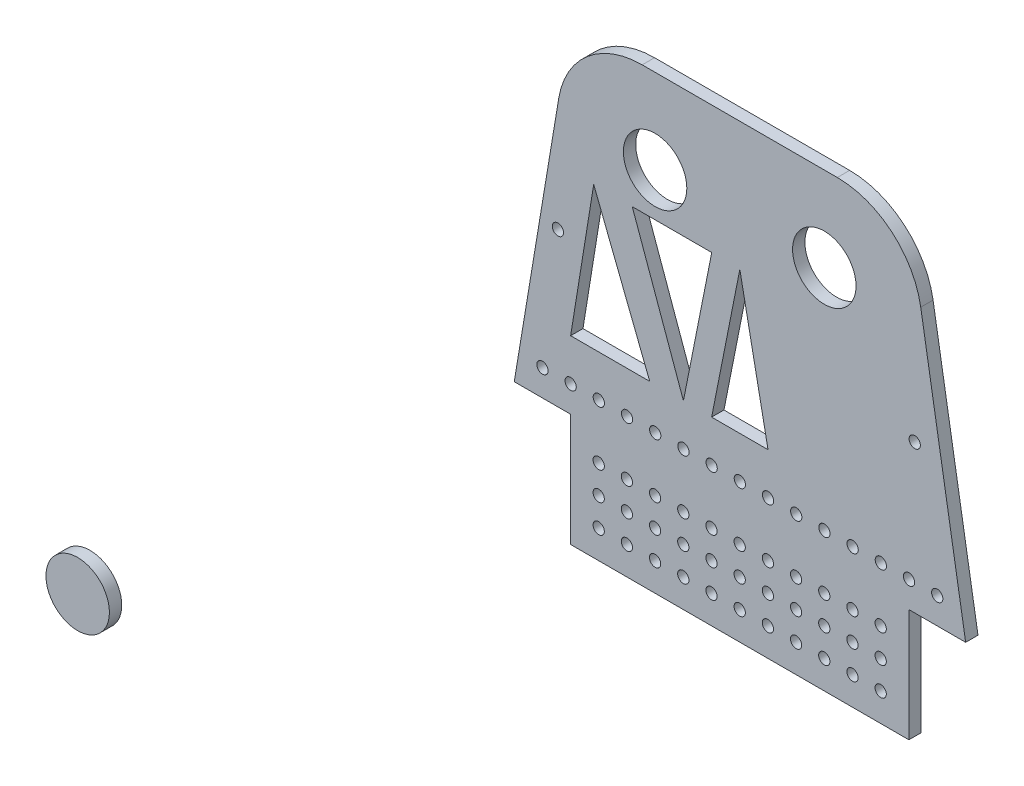
SolidWorks part; units mm, degrees
ref_plane "Front Plane" through (0, 0, 0) normal (0, 0, 1) x (1, 0, 0)
ref_plane "Top Plane" through (0, 0, 0) normal (0, 1, 0) x (1, 0, 0)
ref_plane "Right Plane" through (0, 0, 0) normal (1, 0, 0) x (0, 0, -1)
sketch "Sketch2" plane through (0, 0, 0) normal (0, 0, 1) x (1, 0, 0)
  line L0 (-33.222, -123.0337) -> (-58.5557, -123.0337)
  line L1 (-33.222, 29.3663) -> (119.178, 29.3663)
  line L5 (-58.5557, -123.0337) -> (-33.222, 29.3663)
  line L6 (119.178, -123.0337) -> (144.7459, -123.0337)
  line L7 (144.7459, -123.0337) -> (119.178, 29.3663)
  line L8 (-22.7678, -28.1678) -> (-33.1557, -92.3946)
  line L9 (-33.1557, -92.3946) -> (2.468, -92.3946)
  line L10 (2.468, -92.3946) -> (-22.7678, -28.1678)
  line L14 (43.0443, -28.3997) -> (55.7443, -92.3946)
  line L15 (55.7443, -92.3946) -> (30.3443, -92.3946)
  line L16 (30.3443, -92.3946) -> (43.0443, -28.3997)
  line L20 (17.6443, -92.3946) -> (30.3903, -28.1678)
  line L21 (30.3903, -28.1678) -> (-5.4154, -28.1678)
  line L22 (-5.4154, -28.1678) -> (17.6443, -92.3946)
  line L25 (-33.222, -123.0337) -> (-33.222, -173.8337)
  line L26 (-33.222, -173.8337) -> (119.178, -173.8337)
  line L27 (119.178, -123.0337) -> (119.178, -173.8337)
  circle A0 centre (4.878, -8.7337) radius 14.2875
  circle A1 centre (81.078, -8.7337) radius 14.2875
  circle A2 centre (-45.8557, -111.1877) radius 2.54
  circle A3 centre (-33.1557, -111.1877) radius 2.54
  circle A4 centre (-20.4557, -111.1877) radius 2.54
  circle A5 centre (-7.7557, -111.1877) radius 2.54
  circle A6 centre (4.9443, -111.1877) radius 2.54
  circle A7 centre (17.6443, -111.1877) radius 2.54
  circle A8 centre (30.3443, -111.1877) radius 2.54
  circle A9 centre (43.0443, -111.1877) radius 2.54
  circle A10 centre (55.7443, -111.1877) radius 2.54
  circle A11 centre (68.4443, -111.1877) radius 2.54
  circle A12 centre (81.1443, -111.1877) radius 2.54
  circle A13 centre (93.8443, -111.1877) radius 2.54
  circle A14 centre (106.5443, -111.1877) radius 2.54
  circle A15 centre (119.2443, -111.1877) radius 2.54
  circle A16 centre (131.9443, -111.1877) radius 2.54
  circle A17 centre (-255.1675, -304.1673) radius 14.2875
  circle A18 centre (121.8106, -56.3701) radius 2.54 construction
  circle A19 centre (-38.8741, -53.8301) radius 2.54 construction
  circle A20 centre (121.8106, -56.3701) radius 2.54
  circle A21 centre (-38.8741, -53.8301) radius 2.54
  circle A22 centre (-20.522, -161.1337) radius 2.54
  circle A23 centre (-7.822, -161.1337) radius 2.54
  circle A24 centre (4.878, -161.1337) radius 2.54
  circle A25 centre (17.578, -161.1337) radius 2.54
  circle A26 centre (30.278, -161.1337) radius 2.54
  circle A27 centre (42.978, -161.1337) radius 2.54
  circle A28 centre (55.678, -161.1337) radius 2.54
  circle A29 centre (68.378, -161.1337) radius 2.54
  circle A30 centre (81.078, -161.1337) radius 2.54
  circle A31 centre (93.778, -161.1337) radius 2.54
  circle A32 centre (106.478, -161.1337) radius 2.54
  circle A33 centre (-7.822, -148.4337) radius 2.54
  circle A34 centre (4.878, -148.4337) radius 2.54
  circle A35 centre (17.578, -148.4337) radius 2.54
  circle A36 centre (30.278, -148.4337) radius 2.54
  circle A37 centre (42.978, -148.4337) radius 2.54
  circle A38 centre (55.678, -148.4337) radius 2.54
  circle A39 centre (68.378, -148.4337) radius 2.54
  circle A40 centre (81.078, -148.4337) radius 2.54
  circle A41 centre (93.778, -148.4337) radius 2.54
  circle A42 centre (106.478, -148.4337) radius 2.54
  circle A43 centre (-7.822, -135.7337) radius 2.54
  circle A44 centre (4.878, -135.7337) radius 2.54
  circle A45 centre (17.578, -135.7337) radius 2.54
  circle A46 centre (30.278, -135.7337) radius 2.54
  circle A47 centre (42.978, -135.7337) radius 2.54
  circle A48 centre (55.678, -135.7337) radius 2.54
  circle A49 centre (68.378, -135.7337) radius 2.54
  circle A50 centre (81.078, -135.7337) radius 2.54
  circle A51 centre (93.778, -135.7337) radius 2.54
  circle A52 centre (106.478, -135.7337) radius 2.54
  circle A53 centre (-20.522, -148.4337) radius 2.54
  circle A54 centre (-20.522, -135.7337) radius 2.54
  dimension "D3" = 28.575
  dimension "D4" = 28.575
  dimension "D9" = 15
  dimension "D10" = 12.7
  dimension "D11" = 28.575
  dimension "D13" = 12.7
  dimension "D1" = 152.4
  dimension "D2" = 152.4
  dimension "D5" = 76.2
  dimension "D6" = 38.1
  dimension "D7" = 38.1
  dimension "D8" = 38.1
  dimension "D12" = 50.8
  dimension "D14" = 12.7
  dimension "D15" = 11
  dimension "D16" = 3
extrude "Boss-Extrude1" add sketch "Sketch2" along normal blind 5.5562
fillet "Fillet1" radius 38.1 2 edges at (-33.222, 29.3663, 2.7781) (119.178, 29.3663, 2.7781)
